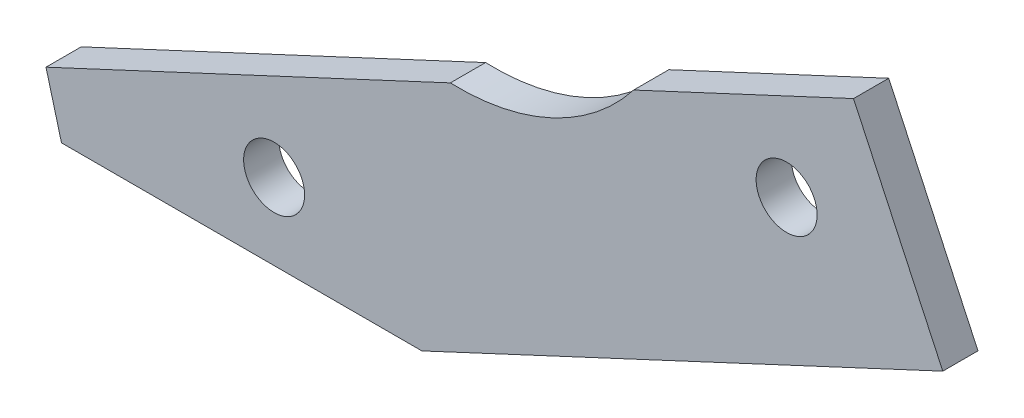
SolidWorks part; units mm, degrees
material "Plain Carbon Steel"
ref_plane "Front Plane" through (0, 0, 0) normal (0, 0, 1) x (1, 0, 0)
ref_plane "Top Plane" through (0, 0, 0) normal (0, 1, 0) x (1, 0, 0)
ref_plane "Right Plane" through (0, 0, 0) normal (1, 0, 0) x (0, 0, -1)
sketch "Sketch3" plane through (0, 0, 0) normal (0, 0, 1) x (1, 0, 0)
  line L0 (-151.3874, 162.947) -> (-171.2181, 153.6997)
  line L1 (-222.8166, 123.7742) -> (-311.2807, 453.927) construction
  line L2 (-224.2135, 128.9876) -> (-222.8166, 123.7742)
  line L3 (-222.8166, 123.7742) -> (-190.3175, 123.7742)
  line L4 (273.7271, 340.1618) -> (-193.6604, 122.2154) construction
  line L5 (-190.3175, 123.7742) -> (-143.3365, 145.6818)
  line L6 (-143.3365, 145.6818) -> (-151.3874, 162.947)
  line L7 (-158.4759, 154.4863) -> (-204.6976, 132.9328) construction
  line L8 (-156.3628, 149.9548) -> (-202.5845, 128.4013) construction
  line L9 (-157.4193, 152.2206) -> (-203.641, 130.667) construction
  line L10 (-156.3628, 149.9548) -> (-158.4759, 154.4863) construction
  line L11 (-202.5845, 128.4013) -> (-204.6976, 132.9328) construction
  line L12 (-178.5531, 147.8519) -> (-171.432, 132.5806) construction
  line L13 (-187.7477, 145.9919) -> (-224.2135, 128.9876)
  circle A0 centre (-157.4193, 152.2206) radius 2.75
  circle A1 centre (-203.641, 130.667) radius 2.75
  arc A2 (-171.2181, 153.6997) -> (-187.7477, 145.9919) centre (-187.0055, 165.9781) cw
  spline S7 degree 3 poles (-159.6851, 151.164) (-157.572, 146.6325) (-153.0405, 148.7456) (-155.1536, 153.2771) (-157.2667, 157.8087) (-161.7982, 155.6956) (-159.6851, 151.164) (-157.572, 146.6325) (-153.0405, 148.7456) knots -0.5 0 0 0 0.5 0.5 0.5 1 1 1 1.5 1.5 1.5 weights 1 0.333333 0.333333 1 0.333333 0.333333 1 0.333333 0.333333 only from (-159.6851, 151.164) to (-159.6851, 151.164) construction
  spline S8 degree 3 poles (-205.9068, 129.6105) (-203.7937, 125.079) (-199.2622, 127.1921) (-201.3753, 131.7236) (-203.4884, 136.2551) (-208.0199, 134.142) (-205.9068, 129.6105) (-203.7937, 125.079) (-199.2622, 127.1921) knots -0.5 0 0 0 0.5 0.5 0.5 1 1 1 1.5 1.5 1.5 weights 1 0.333333 0.333333 1 0.333333 0.333333 1 0.333333 0.333333 only from (-205.9068, 129.6105) to (-205.9068, 129.6105) construction
  dimension "D3" = 5.5
  dimension "D5" = 20
  dimension "D1" = 19.05
  dimension "D2" = 5
  dimension "D4" = 10
  dimension "D6" = 31
  dimension "D7" = 2.2
extrude "Boss-Extrude1" add sketch "Sketch3" against normal blind 3.175
